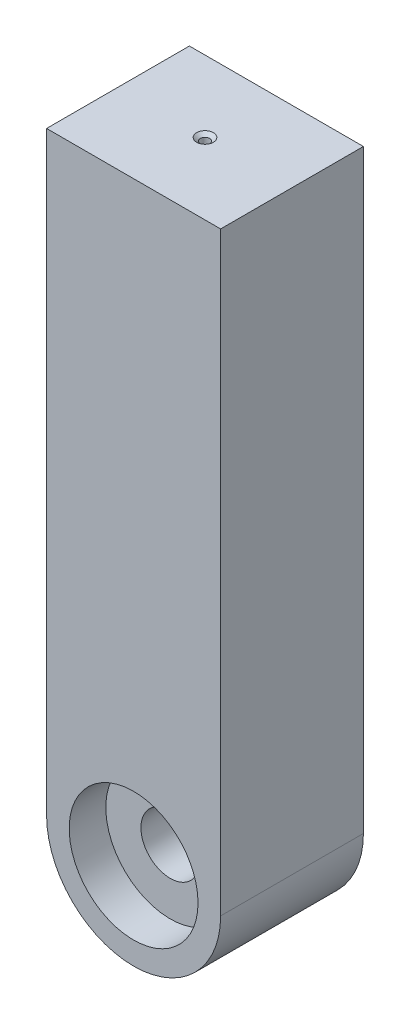
SolidWorks part; units mm, degrees
ref_plane "Front Plane" through (0, 0, 0) normal (0, 0, 1) x (1, 0, 0)
ref_plane "Top Plane" through (0, 0, 0) normal (0, 1, 0) x (1, 0, 0)
ref_plane "Right Plane" through (0, 0, 0) normal (1, 0, 0) x (0, 0, -1)
sketch "Sketch1" plane through (0, 0, 0) normal (0, 0, 1) x (1, 0, 0)
  line L1 (-14.859, 0) -> (-14.859, 101.6)
  line L2 (14.859, 0) -> (14.859, 101.6)
  line L3 (-14.859, 101.6) -> (14.859, 101.6)
  arc A1 (-14.859, 0) -> (14.859, 0) centre (0, 0) ccw
  dimension "D2" = 29.718
  dimension "D3" = 101.6
extrude "Boss-Extrude1" add sketch "Sketch1" along normal blind 24.384
sketch "Sketch4" plane through (0, 101.6, 0) normal (0, 1, 0) x (1, 0, 0)
  circle A0 centre (0, -12.192) radius 2.4653
  point P0 (0, -12.192)
hole_wizard "1/16 (0.0625) Dowel Hole1" positions "Sketch4" profile "Sketch6" hole size "1/16" standard "ANSI Inch" end condition up to next
sketch "Sketch6" plane through (0, 101.6, 12.192) normal (1, 0, 0) x (0, 0, 1)
  line L0 (0, 0) -> (0, 116.459)
  line L1 (0, 116.459) -> (0.7937, 116.459)
  line L2 (0.7937, 116.459) -> (0.7937, 0.5328)
  line L3 (0.7937, 0.5328) -> (1.4287, 0)
  line L5 (1.4287, 0) -> (0, 0)
  line L6 (-0.7938, 0.5328) -> (-1.4287, 0) construction
  line L11 (0, -6.35) -> (0, 107.95) construction
  dimension "Thru Hole Dia." = 1.5875
  dimension "Thru Hole Depth" = 116.459
  dimension "Near C'Sink Dia." = 2.8575
  dimension "Near C'Sink Angle" = 100
sketch "Sketch7" plane through (0, 0, 24.384) normal (0, 0, 1) x (1, 0, 0)
  circle A0 centre (0, 0) radius 11
  dimension "D1" = 22
extrude "Cut-Extrude1" cut sketch "Sketch7" against normal blind 6.25
sketch "Sketch8" plane through (0, 0, 18.134) normal (0, 0, 1) x (1, 0, 0)
  circle A0 centre (0, 0) radius 5
  dimension "D1" = 10
extrude "Cut-Extrude2" cut sketch "Sketch8" against normal blind 33
